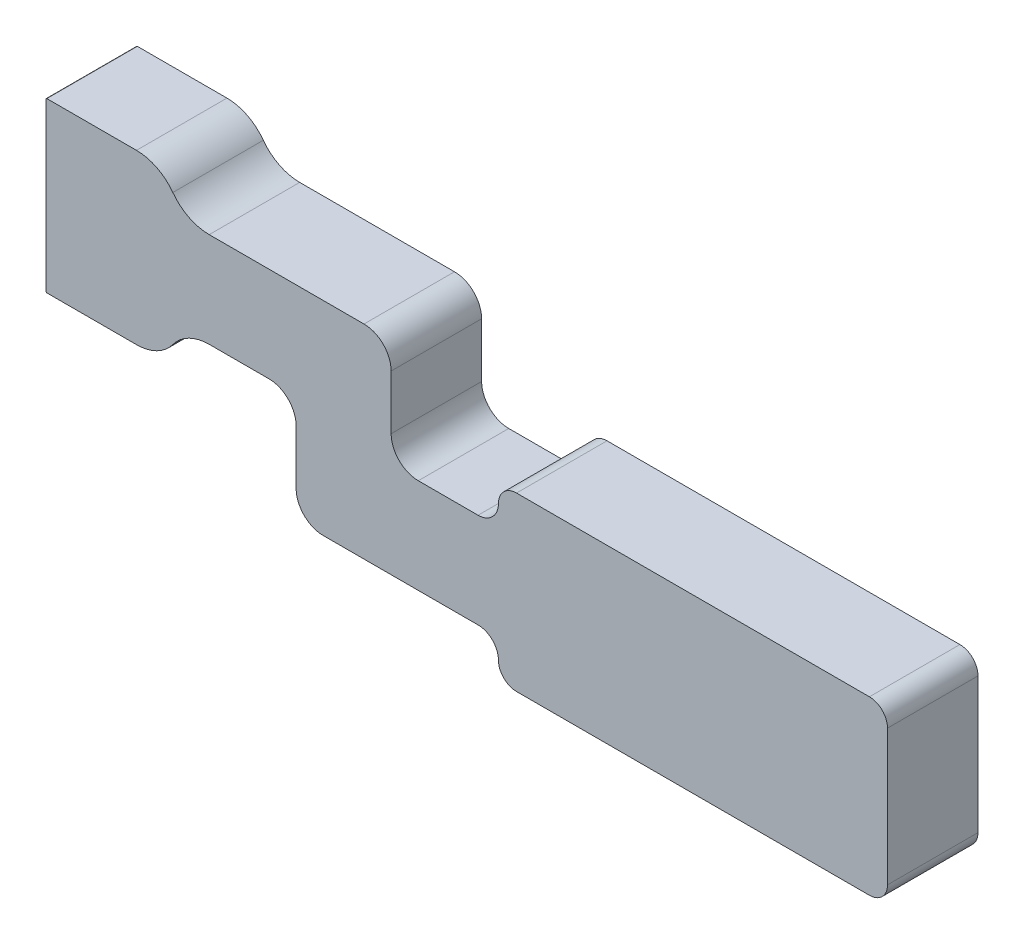
SolidWorks part; units mm, degrees
ref_plane "Front Plane" through (0, 0, 0) normal (1, 0, 0) x (0, 1, 0)
ref_plane "Top Plane" through (0, 0, 0) normal (0, 0, 1) x (0, 1, 0)
ref_plane "Right Plane" through (0, 0, 0) normal (0, 1, 0) x (-1, 0, 0)
sketch "Sketch1" plane through (0, 0, 0) normal (0, 0, 1) x (0, 1, 0)
  line L0 (-7.5, 3) -> (-9.5, 3) construction
  line L1 (-7.5, 43) -> (7.5, 43) construction
  line L2 (-9.5, 41) -> (-9.5, 2)
  line L3 (-7.5, 0) -> (7.5, 0)
  line L4 (9.5, 41) -> (9.5, 2)
  line L5 (-7.5, 3) -> (-7.5, 0) construction
  line L6 (7.5, 3) -> (9.5, 3) construction
  line L7 (-7.5, 38) -> (-7.5, 43) construction
  line L8 (-7.5, 3) -> (-2.5, 3) construction
  line L9 (-2.5, 3) -> (-2.5, 8) construction
  line L10 (6.75, 71.6596) -> (17.25, 71.6596) construction
  line L11 (8.25, 54.8564) -> (14.25, 54.8564)
  line L12 (5.25, 51.8564) -> (5.25, 45.25)
  line L13 (3.75, 65.3564) -> (-2.25, 65.3564)
  line L14 (21.3, 83) -> (21.3, 92.9)
  line L15 (21.2, 93) -> (2.8, 93)
  line L16 (12, 93) -> (12, 74.9627) construction
  line L17 (17.25, 57.8564) -> (17.25, 74.9627)
  line L18 (12, 74.9627) -> (17.25, 74.9627) construction
  line L19 (-5.25, 62.3564) -> (-5.25, 45.25)
  line L20 (-5.25, 53.8032) -> (5.25, 53.8032) construction
  line L21 (-5.25, 53.8032) -> (-9.5, 53.8032) construction
  line L22 (-9.5, 53.8032) -> (-9.5, 43) construction
  line L23 (5.25, 53.8032) -> (9.5, 53.8032) construction
  line L24 (9.5, 53.8032) -> (9.5, 43) construction
  line L25 (2.7, 83) -> (2.7, 92.9)
  line L26 (6.75, 74.9627) -> (6.75, 68.3564)
  line L27 (11.25, 54.8564) -> (11.25, 65.3564) construction
  line L28 (0, 53.8032) -> (0, 43) construction
  circle A0 centre (-7.5, 3) radius 1.25 construction
  circle A1 centre (-2.5, 3) radius 1.25 construction
  circle A2 centre (2.5, 3) radius 1.25 construction
  circle A3 centre (7.5, 3) radius 1.25 construction
  circle A4 centre (-2.5, 8) radius 1.25 construction
  circle A5 centre (2.5, 8) radius 1.25 construction
  circle A6 centre (7.5, 8) radius 1.25 construction
  circle A7 centre (-2.5, 13) radius 1.25 construction
  circle A8 centre (2.5, 13) radius 1.25 construction
  circle A9 centre (7.5, 13) radius 1.25 construction
  circle A10 centre (-2.5, 18) radius 1.25 construction
  circle A11 centre (2.5, 18) radius 1.25 construction
  circle A12 centre (7.5, 18) radius 1.25 construction
  circle A13 centre (-2.5, 23) radius 1.25 construction
  circle A14 centre (2.5, 23) radius 1.25 construction
  circle A15 centre (7.5, 23) radius 1.25 construction
  circle A16 centre (-2.5, 28) radius 1.25 construction
  circle A17 centre (2.5, 28) radius 1.25 construction
  circle A18 centre (7.5, 28) radius 1.25 construction
  circle A19 centre (-2.5, 33) radius 1.25 construction
  circle A20 centre (2.5, 33) radius 1.25 construction
  circle A21 centre (7.5, 33) radius 1.25 construction
  circle A22 centre (-2.5, 38) radius 1.25 construction
  circle A23 centre (2.5, 38) radius 1.25 construction
  circle A24 centre (7.5, 38) radius 1.25 construction
  circle A25 centre (-7.5, 8) radius 1.25 construction
  circle A26 centre (-7.5, 13) radius 1.25 construction
  circle A27 centre (-7.5, 18) radius 1.25 construction
  circle A28 centre (-7.5, 23) radius 1.25 construction
  circle A29 centre (-7.5, 28) radius 1.25 construction
  circle A30 centre (-7.5, 33) radius 1.25 construction
  circle A31 centre (-7.5, 38) radius 1.25 construction
  arc A32 (5.25, 51.8564) -> (8.25, 54.8564) centre (8.25, 51.8564) cw
  arc A33 (14.25, 54.8564) -> (17.25, 57.8564) centre (14.25, 57.8564) ccw
  arc A34 (17.25, 74.9627) -> (19.275, 78.9814) centre (22.25, 74.9627) cw
  arc A35 (19.275, 78.9814) -> (21.3, 83) centre (16.3, 83) ccw
  arc A36 (6.75, 74.9627) -> (4.725, 78.9814) centre (1.75, 74.9627) ccw
  arc A37 (4.725, 78.9814) -> (2.7, 83) centre (7.7, 83) cw
  arc A38 (3.75, 65.3564) -> (6.75, 68.3564) centre (3.75, 68.3564) ccw
  arc A39 (-5.25, 62.3564) -> (-2.25, 65.3564) centre (-2.25, 62.3564) cw
  arc A40 (-7.5, 43) -> (-9.5, 41) centre (-7.5, 41) ccw
  arc A41 (-9.5, 2) -> (-7.5, 0) centre (-7.5, 2) ccw
  arc A42 (7.5, 0) -> (9.5, 2) centre (7.5, 2) ccw
  arc A43 (7.5, 43) -> (9.5, 41) centre (7.5, 41) cw
  arc A44 (-5.25, 45.25) -> (-7.5, 43) centre (-7.5, 45.25) cw
  arc A45 (5.25, 45.25) -> (7.5, 43) centre (7.5, 45.25) ccw
  arc A46 (2.7, 92.9) -> (2.8, 93) centre (2.8, 92.9) cw
  arc A47 (21.3, 92.9) -> (21.2, 93) centre (21.2, 92.9) ccw
  point P0 (0, 0)
  point P112 (0, 51.9008)
  point P121 (9.5, 0)
  point P126 (2.7, 93)
  point P131 (21.3, 93)
  point P132 (12, 75.3078)
  point P133 (12, 70.319)
  dimension "D1" = 2.5
  dimension "D8" = 0.1
  dimension "D7" = 5
  dimension "D10" = 3
  dimension "D14" = 2
  dimension "D15" = 10
  dimension "D2" = 5
  dimension "D3" = 2
  dimension "D6" = 5
  dimension "D9" = 18.6
  dimension "D11" = 50
  dimension "D12" = 2.5
  dimension "D13" = 10.5
  dimension "D16" = 3
  dimension "D4" = 4
  dimension "D5" = 8
extrude "Boss-Extrude2" add sketch "Sketch1" along normal blind 10 contours L14 A47 L15 A46 L25 A37 A36 L26 A38 L13 A39 L19 A44 A40 L2 A41 L3 A42 L4 A43 A45 L12 A32 L11 A33 L17 A34 A35
sketch "Sketch2" plane through (0, 0, 10) normal (0, 0, 1) x (1, 0, 0)
  line L0 (-48.5532, 5.25) -> (-48.5532, -5.25) construction
  line L1 (-51.8564, 5.25) -> (-45.25, 5.25) construction
  line L2 (-62.3564, -5.25) -> (-45.25, -5.25) construction
  line L3 (-66.2351, 5.8713) -> (-55.7351, 16.3713) construction
  line L7 (-74.9627, 17.25) -> (-74.9627, 6.75) construction
  line L9 (-74.9627, 12) -> (-54.8564, 12) construction
  line L11 (-64.4777, -4.3713) -> (-53.9777, 6.1287) construction
  line L12 (-54.8564, 8.25) -> (-54.8564, 14.25) construction
  line L13 (-48.5532, 0) -> (-65.3564, 0) construction
  line L14 (-65.3564, 3.75) -> (-65.3564, -2.25) construction
  line L15 (-61.8637, 12) -> (-60.1064, 10.2426) construction
  line L16 (-58.349, 0) -> (-60.1064, 1.7574) construction
  line L17 (-60.1064, 1.7574) -> (-60.1064, 10.2426) construction
  line L18 (-65.3564, 3.75) -> (-60.1064, 3.75) construction
  line L19 (-54.8564, 8.25) -> (-60.1064, 8.25) construction
  line L20 (0, -7.5) -> (0, 7.5) construction
  line L21 (-41, -9.5) -> (-2, -9.5) construction
  arc A0 (-65.3564, -2.25) -> (-62.3564, -5.25) centre (-62.3564, -2.25) ccw construction
  arc A1 (-54.8564, 8.25) -> (-51.8564, 5.25) centre (-51.8564, 8.25) ccw construction
  arc A2 (-65.3564, 3.75) -> (-68.3564, 6.75) centre (-68.3564, 3.75) ccw construction
  arc A3 (-54.8564, 14.25) -> (-57.8564, 17.25) centre (-57.8564, 14.25) ccw construction
  point P6 (-59.2277, 0.8787)
  point P7 (-48.5532, 0)
  point P16 (-60.9851, 11.1213)
  point P53 (-21.5, -9.5)
  dimension "D1" = 45
  dimension "D2" = 45
  dimension "D3" = 60.1064
  dimension "D4" = 9.5
  dimension "D5" = 21.5
  dimension "D6" = 58.349
  dimension "D7" = 61.8637
